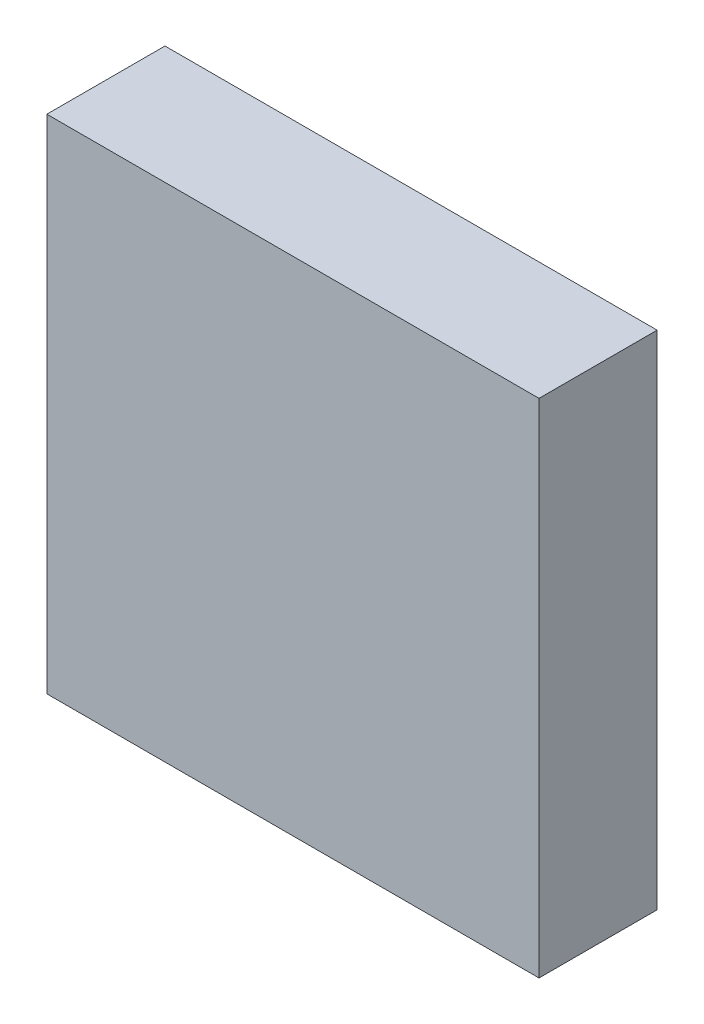
SolidWorks part; units mm, degrees
ref_plane "前视基准面" through (0, 0, 0) normal (0, 0, 1) x (1, 0, 0)
ref_plane "上视基准面" through (0, 0, 0) normal (0, 1, 0) x (1, 0, 0)
ref_plane "右视基准面" through (0, 0, 0) normal (1, 0, 0) x (0, 0, -1)
sketch "草图1" plane through (0, 0, 0) normal (0, 0, 1) x (1, 0, 0)
  line L1 (0, 0) -> (50, 0)
  line L2 (0, 0) -> (0, -51)
  line L3 (0, -51) -> (50, -51)
  line L4 (50, 0) -> (50, -51)
  dimension "D1" = 50
  dimension "D2" = 51
extrude "凸台-拉伸1" add sketch "草图1" along normal blind 12
